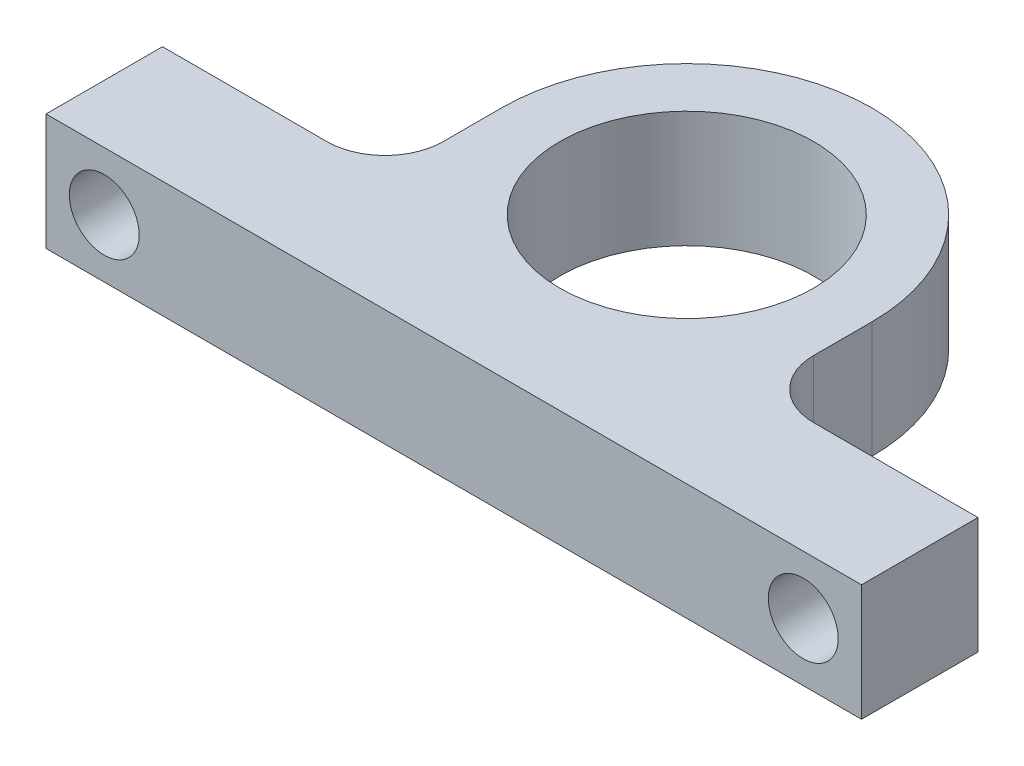
SolidWorks part; units mm, degrees
ref_plane "Front Plane" through (0, 0, 0) normal (0, 0, 1) x (1, 0, 0)
ref_plane "Top Plane" through (0, 0, 0) normal (0, 1, 0) x (1, 0, 0)
ref_plane "Right Plane" through (0, 0, 0) normal (1, 0, 0) x (0, 0, -1)
sketch "Sketch1" plane through (0, 0, 0) normal (0, 1, 0) x (1, 0, 0)
  line L0 (0, 0) -> (0, 20) construction
  line L5 (35, 0) -> (-35, 0)
  line L6 (-35, 0) -> (-35, 10)
  line L7 (-15.9, 10) -> (-35, 10)
  line L8 (-15.9, 20) -> (-15.9, 10)
  line L9 (0, 20) -> (0, 120.2965) construction
  line L10 (15.9, 20) -> (15.9, 10)
  line L11 (15.9, 10) -> (35, 10)
  line L12 (35, 0) -> (35, 10)
  circle A0 centre (0, 20) radius 10.9
  arc A1 (15.9, 20) -> (-15.9, 20) centre (0, 20) ccw
  dimension "D1" = 21.8
  dimension "D2" = 35
  dimension "D4" = 5
  dimension "D3" = 10
  dimension "D5" = 10
extrude "Boss-Extrude1" add sketch "Sketch1" along normal blind 10
fillet "Fillet1" radius 5 2 edges at (-15.9, 5, -10) (15.9, 5, -10)
sketch "Sketch2" plane through (0, 0, -10) normal (0, 0, -1) x (-1, 0, 0)
  line L0 (0, 0) -> (0, 10) construction
  line L1 (-15.9, 0) -> (15.9, 0) construction
  line L2 (15.9, 10) -> (-15.9, 10) construction
  line L3 (-35, 10) -> (-20.9, 10) construction
  line L4 (-35, 10) -> (-35, 0) construction
  circle A0 centre (-30, 5) radius 3
  circle A1 centre (30, 5) radius 3
  point P0 (-30, 5)
  point P8 (30, 5)
  dimension "D3" = 6
  dimension "D1" = 5
  dimension "D2" = 5
extrude "Cut-Extrude1" cut sketch "Sketch2" against normal through all
